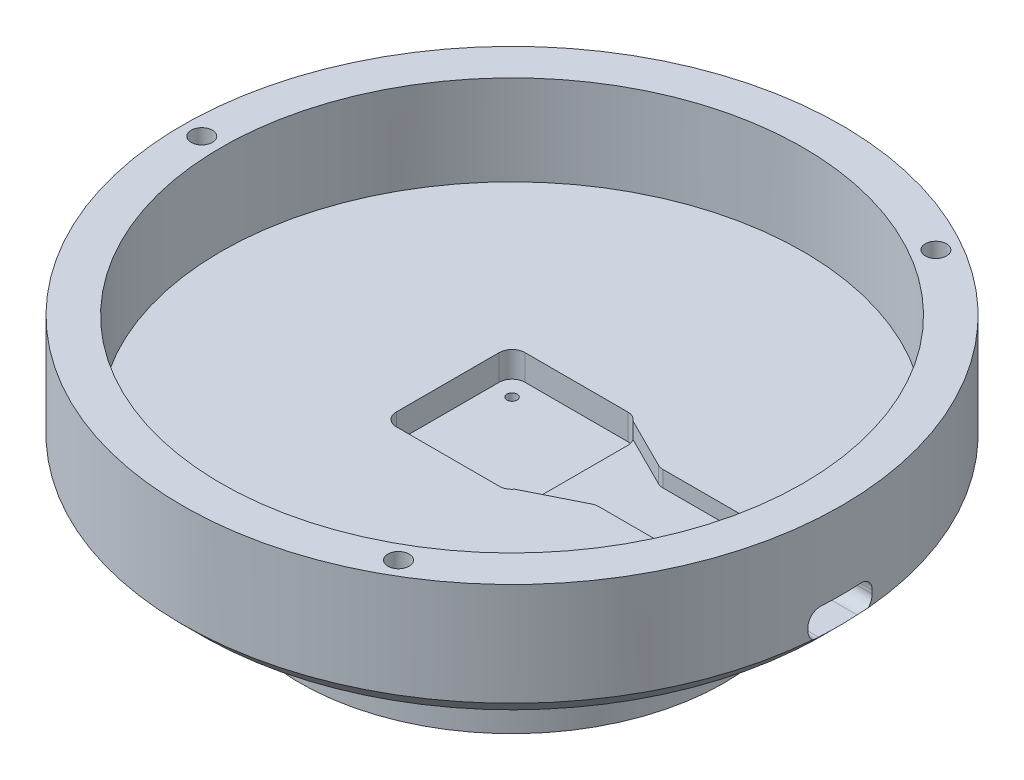
SolidWorks part; units mm, degrees
material "PVC"
ref_plane "Front" through (0, 0, 0) normal (0, 0, 1) x (1, 0, 0)
ref_plane "Top" through (0, 0, 0) normal (0, 1, 0) x (1, 0, 0)
ref_plane "Right" through (0, 0, 0) normal (1, 0, 0) x (0, 0, -1)
sketch "Esquisse1" plane through (0, 0, 0) normal (0, 0, 1) x (1, 0, 0)
  line L0 (0, 0) -> (0, 33) construction
  line L1 (0, 11.5) -> (31, 11.5)
  line L2 (31, 11.5) -> (31, 0)
  line L3 (31, 0) -> (33, 0)
  line L4 (33, 0) -> (33, 14)
  line L5 (33, 14) -> (51.25, 14)
  line L6 (51.25, 14) -> (51.25, 33)
  line L7 (51.25, 33) -> (45.25, 33)
  line L8 (45.25, 33) -> (45.25, 19)
  line L9 (45.25, 19) -> (0, 19)
  line L10 (0, 19) -> (0, 11.5)
  point P13 (48.25, 33)
  dimension "D1" = 14
  dimension "D2" = 90.5
  dimension "D3" = 6
  dimension "D4" = 2
  dimension "D5" = 62
  dimension "D6" = 14
  dimension "D7" = 7.5
  dimension "D8" = 11.5
revolve "Révolution1" add sketch "Esquisse1" angle 360 about L0
hole_wizard "Trou pour taraudage pour trou taraudé M41" positions "Esquisse2" profile "Esquisse3" hole size "M4" standard "ISO"
sketch "Esquisse2" plane through (0, 33, 0) normal (0, 1, 0) x (1, 0, 0)
  line L0 (-48.25, 0) -> (0, 0) construction
  line L1 (0, 0) -> (24.125, 41.7857) construction
  line L3 (24.125, -41.7857) -> (0, 0) construction
  line L5 (45.25, 0) -> (51.25, 0) construction
  circle A0 centre (0, 0) radius 45.25 construction
  circle A1 centre (0, 0) radius 51.25 construction
  circle A2 centre (0, 0) radius 48.25 construction
  point P0 (-48.25, 0)
  point P6 (24.125, 41.7857)
  point P7 (24.125, -41.7857)
  point P33 (48.25, 0)
  dimension "D1" = 3
sketch "Esquisse3" plane through (-48.25, 33, 0) normal (1, 0, 0) x (0, 0, 1)
  line L0 (0, 0) -> (0, 10)
  line L1 (0, 10) -> (1.65, 10)
  line L2 (1.65, 10) -> (1.65, 0)
  line L5 (1.65, 0) -> (0, 0)
  line L10 (0, 10) -> (-1.65, 10) construction
  line L11 (0, -6.35) -> (0, 107.95) construction
  dimension "Diamètre du perçage" = 3.3
  dimension "Profondeur du perçage" = 10
  dimension "Angle de pointe" = 180
chamfer "Chanfrein1" distance 3 angle 45 1 edges at (51.25, 14, 0)
sketch "Esquisse4" plane through (0, 19, 0) normal (0, 1, 0) x (1, 0, 0)
  line L1 (-8, 10) -> (8, 10)
  line L2 (-10, 8) -> (-10, -8)
  line L3 (-8, -10) -> (8, -10)
  line L4 (10, 8) -> (10, -8)
  line L5 (-10, 10) -> (10, -10) construction
  line L6 (-10, -10) -> (10, 10) construction
  arc A0 (-10, -8) -> (-8, -10) centre (-8, -8) ccw
  arc A1 (8, -10) -> (10, -8) centre (8, -8) ccw
  arc A2 (10, 8) -> (8, 10) centre (8, 8) ccw
  arc A3 (-8, 10) -> (-10, 8) centre (-8, 8) ccw
  point P0 (0, 0)
  dimension "D3" = 2
  dimension "D1" = 20
  dimension "D2" = 20
extrude "Enlèv. mat.-Extru.1" cut sketch "Esquisse4" against normal blind 4
sketch "Esquisse5" plane through (0, 19, 0) normal (0, 1, 0) x (1, 0, 0)
  line L5 (8, -10) -> (17.5777, -5.2111)
  line L6 (18.4721, -5) -> (43.1458, -5)
  line L8 (43.1458, 5) -> (18.4721, 5)
  line L9 (17.5777, 5.2111) -> (8, 10)
  line L10 (8, 10) -> (8, -10)
  line L11 (0, 0) -> (51.25, 0) construction
  line L12 (18, -5) -> (18, 0) construction
  line L13 (18, 0) -> (18, 5) construction
  line L14 (10, -8) -> (10, 8) construction
  circle A0 centre (0, 0) radius 51.25 construction
  circle A3 centre (0, 0) radius 45.25 construction
  arc A4 (45.141, 3.1387) -> (45.141, -3.1387) centre (0, 0) cw
  arc A5 (43.1458, -5) -> (45.141, -3.1387) centre (43.1458, -3) ccw
  arc A6 (45.141, 3.1387) -> (43.1458, 5) centre (43.1458, 3) ccw
  arc A7 (17.5777, -5.2111) -> (18.4721, -5) centre (18.4721, -7) cw
  arc A8 (18.4721, 5) -> (17.5777, 5.2111) centre (18.4721, 7) cw
  point P22 (44.9729, -5)
  point P25 (44.9729, 5)
  dimension "D3" = 2
  dimension "D1" = 10
  dimension "D2" = 8
extrude "Enlèv. mat.-Extru.2" cut sketch "Esquisse5" against normal blind 2.5
hole_wizard "Trou pour taraudage pour trou taraudé M21" positions "Esquisse6" profile "Esquisse7" hole size "M2" standard "ISO" end condition through all
sketch "Esquisse6" plane through (0, 15, 0) normal (0, 1, 0) x (1, 0, 0)
  line L0 (0, 0) -> (-7, 0) construction
  line L2 (-7, 7) -> (-7, -7) construction
  point P0 (-7, 7)
  point P2 (-7, -7)
  point P16 (-7, 0)
  dimension "D1" = 14
  dimension "D2" = 7
sketch "Esquisse7" plane through (-7, 15, -7) normal (1, 0, 0) x (0, 0, 1)
  line L0 (0, 0) -> (0, 15)
  line L1 (0, 15) -> (0.8, 15)
  line L2 (0.8, 15) -> (0.8, 0)
  line L5 (0.8, 0) -> (0, 0)
  line L11 (0, -6.35) -> (0, 107.95) construction
  dimension "Diamètre du perçage jusqu'au prochain" = 1.6
  dimension "Profondeur du perçage jusqu'au prochain" = 15
ref_plane "Plan1" through (51.25, 0, 0) normal (1, 0, 0) x (0, 0, -1)
sketch "Esquisse8" plane through (51.25, 0, 0) normal (1, 0, 0) x (0, 0, -1)
  line L0 (3.1387, 16.5) -> (-3.1387, 16.5) construction
  line L1 (-3, 21) -> (3, 21)
  line L2 (-5, 19) -> (-5, 18.5)
  line L3 (-3, 16.5) -> (3, 16.5)
  line L4 (5, 19) -> (5, 18.5)
  line L5 (-5, 21) -> (5, 16.5) construction
  line L6 (-5, 16.5) -> (5, 21) construction
  arc A0 (-3, 21) -> (-5, 19) centre (-3, 19) ccw
  arc A1 (5, 19) -> (3, 21) centre (3, 19) ccw
  arc A2 (-3, 16.5) -> (-5, 18.5) centre (-3, 18.5) cw
  arc A3 (3, 16.5) -> (5, 18.5) centre (3, 18.5) ccw
  point P0 (0, 18.75)
  dimension "D3" = 2
  dimension "D4" = 2
  dimension "D5" = 2
  dimension "D1" = 4.5
  dimension "D2" = 10
extrude "Enlèv. mat.-Extru.3" cut sketch "Esquisse8" against normal up to next
